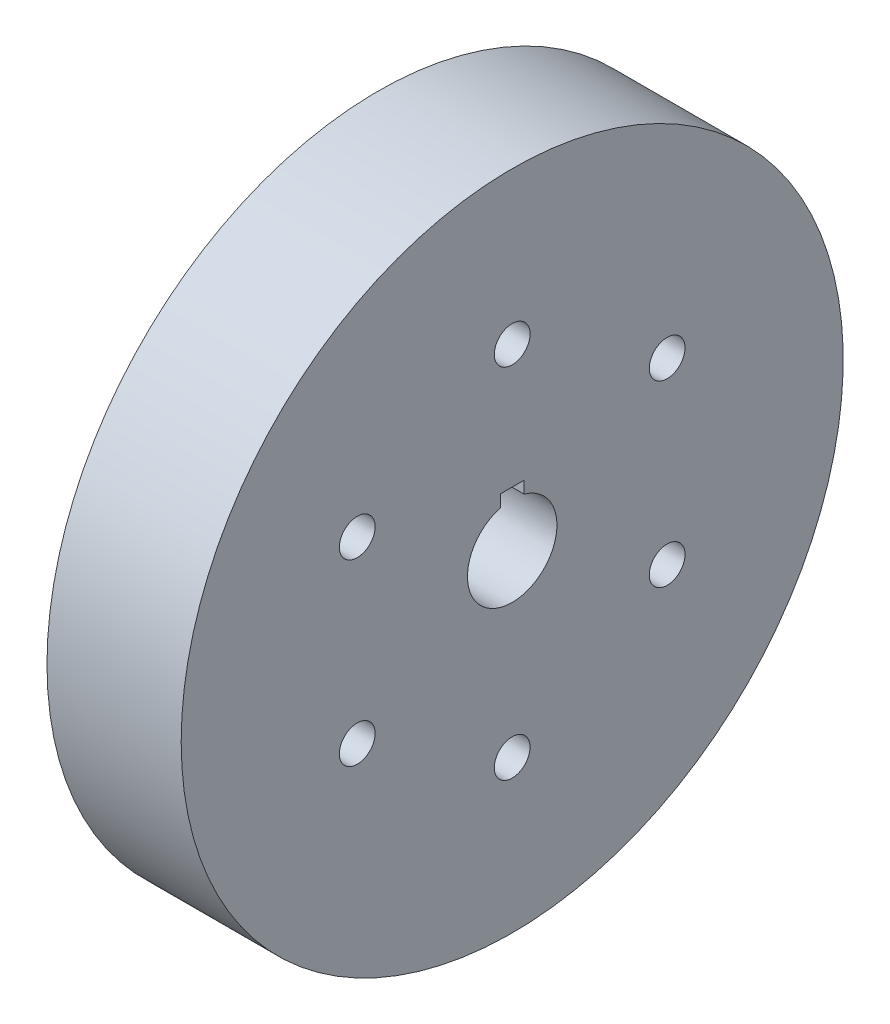
SolidWorks part; units mm, degrees
ref_plane "Front Plane" through (0, 0, 0) normal (0, 0, 1) x (1, 0, 0)
ref_plane "Top Plane" through (0, 0, 0) normal (0, 1, 0) x (1, 0, 0)
ref_plane "Right Plane" through (0, 0, 0) normal (1, 0, 0) x (0, 0, -1)
sketch "Sketch2" plane through (0, 0, 0) normal (0, 1, 0) x (1, 0, 0)
  line L0 (-2282.9916, 0) -> (-70, 0) construction
  line L1 (0, -2282.9916) -> (0, 0) construction
  line L2 (0, 15) -> (0, 111)
  line L3 (0, 111) -> (-45, 111)
  line L4 (-45, 111) -> (-45, 96)
  line L5 (-45, 96) -> (-40, 96)
  line L6 (-35, 91) -> (-35, 35)
  line L7 (-40, 30) -> (-70, 30)
  line L8 (-70, 30) -> (-70, 15)
  line L10 (-70, 15) -> (0, 15)
  line L11 (0, 0) -> (111866.589, 0) construction
  line L12 (0, 15) -> (0, 111866.589) construction
  arc A0 (-35, 91) -> (-40, 96) centre (-40, 91) ccw
  arc A1 (-35, 35) -> (-40, 30) centre (-40, 35) cw
  point P17 (-35, 96)
  dimension "D7" = 5
  dimension "D11" = 5
  dimension "D1" = 15
  dimension "D2" = 30
  dimension "D3" = 70
  dimension "D4" = 35
  dimension "D5" = 10
  dimension "D6" = 45
  dimension "D8" = 111
  dimension "D9" = 96
  dimension "D10" = 35
revolve "Revolve3" add sketch "Sketch2" angle 360 about L11
sketch "Sketch5" plane through (-70, 0, 0) normal (-1, 0, 0) x (0, 0, 1)
  line L0 (0, 111) -> (0, -111) construction
  line L1 (-111, 0) -> (111, 0) construction
  line L2 (0, 0) -> (96.1288, 55.5) construction
  line L3 (0, 0) -> (-96.1288, 55.5) construction
  line L4 (0, 0) -> (96.1288, -55.5) construction
  line L5 (0, 0) -> (-96.1288, -55.5) construction
  line L6 (21.425, 20.9993) -> (68.5599, 67.1978) construction
  line L8 (-4, 11.5) -> (4, 11.5)
  line L9 (-4, 11.5) -> (-4, 18.5)
  line L10 (-4, 18.5) -> (4, 18.5)
  line L11 (4, 11.5) -> (4, 18.5)
  line L12 (-4, 11.5) -> (4, 18.5) construction
  line L13 (-4, 18.5) -> (4, 11.5) construction
  circle A0 centre (0, 0) radius 111 construction
  circle A1 centre (0, 0) radius 30 construction
  circle A2 centre (0, 0) radius 96 construction
  circle A3 centre (0, 0) radius 63 construction
  circle A4 centre (54.5596, 31.5) radius 6
  circle A5 centre (54.5596, -31.5) radius 6
  circle A6 centre (-54.5596, -31.5) radius 6
  circle A7 centre (-54.5596, 31.5) radius 6
  circle A8 centre (0, 63) radius 6
  circle A9 centre (0, -63) radius 6
  circle A10 centre (0, 0) radius 15 construction
  point P20 (44.9924, 44.0985)
  point P33 (0, 15)
  point P40 (0, 0)
  dimension "D2" = 7
  dimension "D1" = 30
  dimension "D3" = 8
extrude "Cut-Extrude5" cut sketch "Sketch5" against normal through all contours L9 L8 L11 L10
sketch "Sketch12" plane through (-35, 0, 0) normal (-1, 0, 0) x (0, 0, 1)
  line L0 (0, -1000) -> (0, 49000) construction
  line L1 (0, 0) -> (96.1288, 55.5) construction
  line L2 (-1000, 0) -> (49000, 0) construction
  circle A0 centre (0, 0) radius 111 construction
  circle A1 centre (51.9615, 30) radius 6
  circle A2 centre (-51.9615, 30) radius 6
  circle A3 centre (51.9615, -30) radius 6
  circle A4 centre (-51.9615, -30) radius 6
  circle A5 centre (0, 60) radius 6
  circle A6 centre (0, -60) radius 6
  dimension "D2" = 60
  dimension "D3" = 60
  dimension "D1" = 60
extrude "Cut-Extrude6" cut sketch "Sketch12" against normal through all
